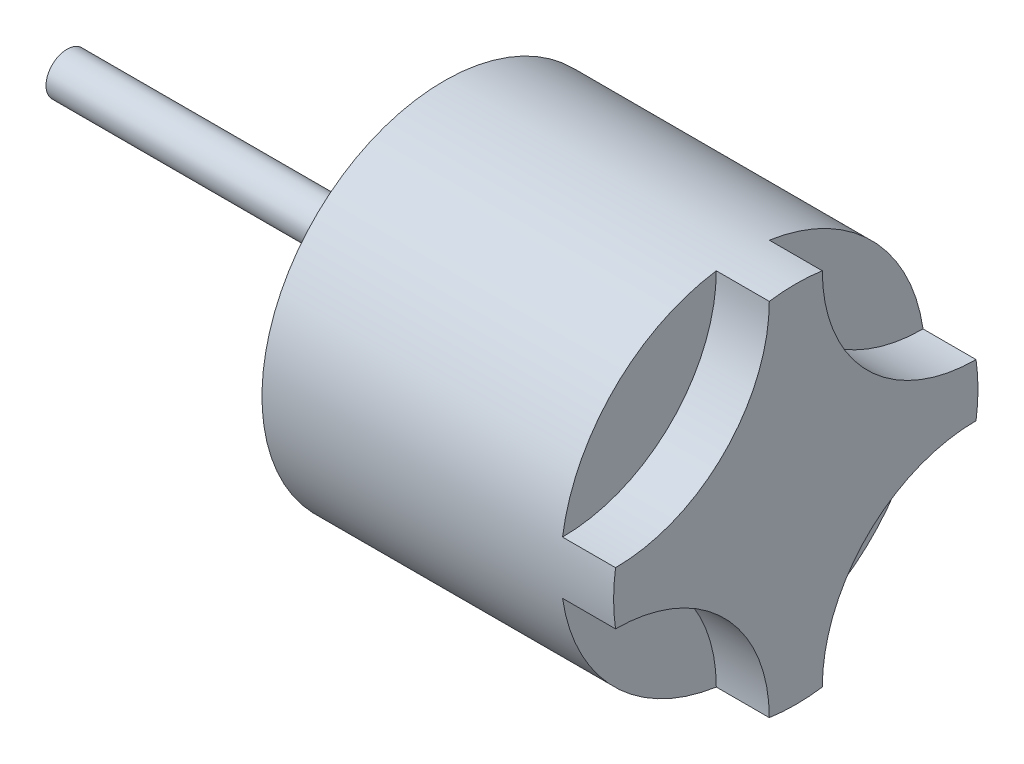
SolidWorks part; units mm, degrees
ref_plane "Front Plane" through (0, 0, 0) normal (0, 0, 1) x (1, 0, 0)
ref_plane "Top Plane" through (0, 0, 0) normal (0, 1, 0) x (1, 0, 0)
ref_plane "Right Plane" through (0, 0, 0) normal (1, 0, 0) x (0, 0, -1)
sketch "Sketch1" plane through (0, 0, 0) normal (1, 0, 0) x (0, 0, -1)
  circle A0 centre (0, 0) radius 13.75
  dimension "D1" = 27.5
extrude "Boss-Extrude1" add sketch "Sketch1" along normal blind 30
sketch "Sketch2" plane through (0, 0, 0) normal (-1, 0, 0) x (0, 0, 1)
  circle A0 centre (0, 0) radius 1.585
  dimension "D1" = 3.17
extrude "Boss-Extrude2" add sketch "Sketch2" along normal blind 25
chamfer "Chamfer1" distance 6 angle 30 1 edges at (0, 0, -13.75)
sketch "Sketch3" plane through (30, 0, 0) normal (1, 0, 0) x (0, 0, -1)
  line L0 (-2, 1.5785) -> (-2, -2.5445) construction
  line L1 (1.0254, 2) -> (-3.6705, 2) construction
  arc A0 (-2, 13.6038) -> (-13.6038, 2) centre (-13.6038, 13.6038) cw
  circle A1 centre (0, 0) radius 13.75 construction
  arc A2 (-2, 13.6038) -> (-13.6038, 2) centre (0, 0) ccw
  dimension "D1" = 2
  dimension "D3" = 11.6038
  dimension "D2" = 2
extrude "Cut-Extrude1" cut sketch "Sketch3" against normal blind 4
mirror "Mirror1" about plane through (0, 0, 0) normal (0, 0, 1) of "Cut-Extrude1"
mirror "Mirror2" about plane through (0, 0, 0) normal (0, 1, 0) of "Mirror1", "Cut-Extrude1"
